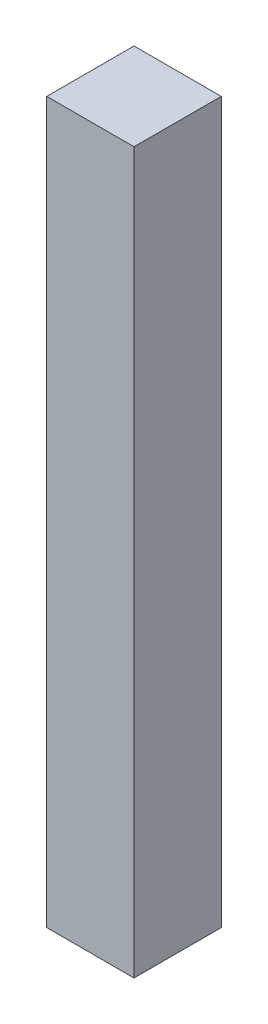
SolidWorks part; units mm, degrees
ref_plane "Front Plane" through (0, 0, 0) normal (0, 0, 1) x (1, 0, 0)
ref_plane "Top Plane" through (0, 0, 0) normal (0, 1, 0) x (1, 0, 0)
ref_plane "Right Plane" through (0, 0, 0) normal (1, 0, 0) x (0, 0, -1)
sketch "Sketch1" plane through (0, 0, 0) normal (0, 1, 0) x (1, 0, 0)
  line L1 (-40, 40) -> (40, 40)
  line L2 (-40, 40) -> (-40, -40)
  line L3 (-40, -40) -> (40, -40)
  line L4 (40, 40) -> (40, -40)
  line L5 (-40, 40) -> (40, -40) construction
  line L6 (-40, -40) -> (40, 40) construction
  point P0 (0, 0)
  dimension "D1" = 80
  dimension "D2" = 80
extrude "Boss-Extrude1" add sketch "Sketch1" along normal blind 660
sketch "Sketch2" plane through (0, 0, 0) normal (0, -1, 0) x (1, 0, 0)
  circle A0 centre (0, 0) radius 9
  dimension "D1" = 18
extrude "Cut-Extrude1" cut sketch "Sketch2" against normal blind 590
